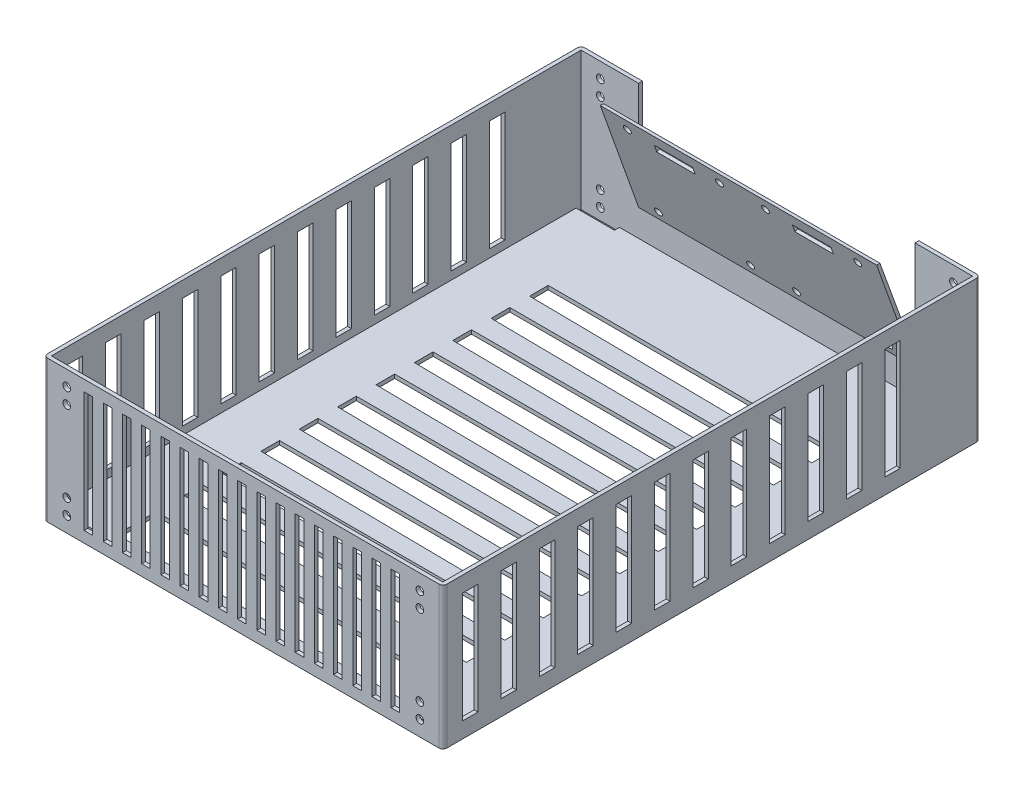
SolidWorks part; units mm, degrees
ref_plane "Front Plane" through (0, 0, 0) normal (0, 0, 1) x (1, 0, 0)
ref_plane "Top Plane" through (0, 0, 0) normal (0, 1, 0) x (1, 0, 0)
ref_plane "Right Plane" through (0, 0, 0) normal (1, 0, 0) x (0, 0, -1)
sketch "Sketch2" plane through (0, 0, 0) normal (0, 1, 0) x (1, 0, 0)
  line L1 (-52, -70) -> (52, -70)
  line L2 (-52, -70) -> (-52, 70)
  line L3 (-52, 70) -> (52, 70)
  line L4 (52, -70) -> (52, 70)
  line L5 (-52, -70) -> (52, 70) construction
  line L6 (-52, 70) -> (52, -70) construction
  point P0 (0, 0)
  dimension "D1" = 104
  dimension "D2" = 140
extrude "Boss-Extrude1" add sketch "Sketch2" along normal blind 1
sketch "Sketch3" plane through (0, 1, 0) normal (0, 1, 0) x (1, 0, 0)
  line L10 (-52, 70) -> (52, 70)
  line L11 (52, 70) -> (52, -70)
  line L12 (52, -70) -> (-52, -70)
  line L13 (-52, -70) -> (-52, 70)
  line L18 (-51, -69) -> (51, -69)
  line L19 (51, -69) -> (51, 69)
  line L20 (51, 69) -> (-51, 69)
  line L21 (-51, 69) -> (-51, -69)
  point P4 (0, -70)
  point P5 (0, -69)
  dimension "D2" = 1
  dimension "D1" = 1
  dimension "D3" = 1
  dimension "D4" = 1
extrude "Boss-Extrude2" add sketch "Sketch3" along normal blind 35 and the other way blind 2
sketch "Sketch4" plane through (0, -1, 0) normal (0, -1, 0) x (1, 0, 0)
  line L18 (-51, 69) -> (51, 69)
  line L19 (-51, 69) -> (51, 69) construction
  line L20 (51, 69) -> (51, -69)
  line L21 (51, -69) -> (-51, -69)
  line L22 (-51.5, 69.5) -> (-51.5, -69.5)
  line L23 (-51.5, -69.5) -> (51.5, -69.5)
  line L24 (51.5, 69.5) -> (-51.5, 69.5)
  line L25 (51.5, -69.5) -> (51.5, 69.5)
  line L26 (-51.5, 69.5) -> (-51.5, -69.5)
  line L27 (-51.5, -69.5) -> (51.5, -69.5)
  line L28 (51.5, 69.5) -> (-51.5, 69.5)
  line L29 (51.5, -69.5) -> (51.5, 69.5)
  line L30 (-51, -69) -> (-51, 69)
  dimension "D1" = 0.5
extrude "Cut-Extrude1" cut sketch "Sketch4" against normal blind 1
fillet "Fillet1" radius 1 4 edges at (-52, 17.5, 70) (-52, 17.5, -70) (52, 17.5, -70) (52, 17.5, 70)
sketch "Sketch5" plane through (0, 0, -70) normal (0, 0, -1) x (-1, 0, 0)
  line L0 (51, -1) -> (51, 10)
  line L1 (51, -1) -> (51, 36) construction
  line L2 (51, 10) -> (41, 10)
  line L3 (41, 10) -> (41, -1)
  line L4 (-51, -1) -> (51, -1) construction
  line L5 (41, -1) -> (51, -1)
  line L6 (46, 10) -> (46, -1) construction
  line L7 (41, 3) -> (51, 3) construction
  line L8 (41, 7) -> (51, 7) construction
  line L9 (0, -1) -> (0, 36) construction
  line L10 (-51, 36) -> (51, 36) construction
  line L11 (51, 17.5) -> (0, 17.5) construction
  line L12 (0, 17.5) -> (-51.1366, 17.5) construction
  circle A0 centre (46, 7) radius 1
  circle A1 centre (46, 3) radius 1
  circle A2 centre (-46, 3) radius 1
  circle A3 centre (-46, 7) radius 1
  circle A4 centre (46, 32) radius 1
  circle A5 centre (46, 28) radius 1
  circle A6 centre (-46, 32) radius 1
  circle A7 centre (-46, 28) radius 1
  point P38 (0, 0)
  point P39 (0, 0)
  point P40 (0, 0)
  point P41 (0, 0)
  dimension "D5" = 2
  dimension "D6" = 2
  dimension "D1" = 10
  dimension "D2" = 11
  dimension "D3" = 3
  dimension "D4" = 4
extrude "Cut-Extrude2" cut sketch "Sketch5" against normal through all contours A2 | A0 | A1 | A4 | A3 | A7 | A6 | A5
sketch "Sketch6" plane through (52, 0, 0) normal (1, 0, 0) x (0, 0, -1)
  line L0 (-64.8795, 31.9235) -> (-64.8795, 3.0765)
  line L5 (-64.8795, 3.0765) -> (-60.8489, 3.0765)
  line L6 (-60.8489, 3.0765) -> (-60.8489, 31.9235)
  line L7 (-60.8489, 31.9235) -> (-64.8795, 31.9235)
  line L8 (-62.8642, 36) -> (-62.8642, 31.9235) construction
  line L9 (-69, 36) -> (69, 36) construction
  line L10 (-62.8642, 3.0765) -> (-62.8642, -1) construction
  line L11 (-69, -1) -> (69, -1) construction
  line L12 (-50.8489, 31.9235) -> (-54.8795, 31.9235)
  line L13 (-54.8795, 31.9235) -> (-54.8795, 3.0765)
  line L14 (-54.8795, 3.0765) -> (-50.8489, 3.0765)
  line L15 (-50.8489, 3.0765) -> (-50.8489, 31.9235)
  line L16 (-40.8489, 31.9235) -> (-44.8795, 31.9235)
  line L17 (-44.8795, 31.9235) -> (-44.8795, 3.0765)
  line L18 (-44.8795, 3.0765) -> (-40.8489, 3.0765)
  line L19 (-40.8489, 3.0765) -> (-40.8489, 31.9235)
  line L20 (-30.8489, 31.9235) -> (-34.8795, 31.9235)
  line L21 (-34.8795, 31.9235) -> (-34.8795, 3.0765)
  line L22 (-34.8795, 3.0765) -> (-30.8489, 3.0765)
  line L23 (-30.8489, 3.0765) -> (-30.8489, 31.9235)
  line L24 (-20.8489, 31.9235) -> (-24.8795, 31.9235)
  line L25 (-24.8795, 31.9235) -> (-24.8795, 3.0765)
  line L26 (-24.8795, 3.0765) -> (-20.8489, 3.0765)
  line L27 (-20.8489, 3.0765) -> (-20.8489, 31.9235)
  line L28 (-10.8489, 31.9235) -> (-14.8795, 31.9235)
  line L29 (-14.8795, 31.9235) -> (-14.8795, 3.0765)
  line L30 (-14.8795, 3.0765) -> (-10.8489, 3.0765)
  line L31 (-10.8489, 3.0765) -> (-10.8489, 31.9235)
  line L32 (-0.8489, 31.9235) -> (-4.8795, 31.9235)
  line L33 (-4.8795, 31.9235) -> (-4.8795, 3.0765)
  line L34 (-4.8795, 3.0765) -> (-0.8489, 3.0765)
  line L35 (-0.8489, 3.0765) -> (-0.8489, 31.9235)
  line L36 (9.1511, 31.9235) -> (5.1205, 31.9235)
  line L37 (5.1205, 31.9235) -> (5.1205, 3.0765)
  line L38 (5.1205, 3.0765) -> (9.1511, 3.0765)
  line L39 (9.1511, 3.0765) -> (9.1511, 31.9235)
  line L40 (19.1511, 31.9235) -> (15.1205, 31.9235)
  line L41 (15.1205, 31.9235) -> (15.1205, 3.0765)
  line L42 (15.1205, 3.0765) -> (19.1511, 3.0765)
  line L43 (19.1511, 3.0765) -> (19.1511, 31.9235)
  line L44 (29.1511, 31.9235) -> (25.1205, 31.9235)
  line L45 (25.1205, 31.9235) -> (25.1205, 3.0765)
  line L46 (25.1205, 3.0765) -> (29.1511, 3.0765)
  line L47 (29.1511, 3.0765) -> (29.1511, 31.9235)
  line L48 (39.1511, 31.9235) -> (35.1205, 31.9235)
  line L49 (35.1205, 31.9235) -> (35.1205, 3.0765)
  line L50 (35.1205, 3.0765) -> (39.1511, 3.0765)
  line L51 (39.1511, 3.0765) -> (39.1511, 31.9235)
  line L52 (49.1511, 31.9235) -> (45.1205, 31.9235)
  line L53 (45.1205, 31.9235) -> (45.1205, 3.0765)
  line L54 (45.1205, 3.0765) -> (49.1511, 3.0765)
  line L55 (49.1511, 3.0765) -> (49.1511, 31.9235)
  line L60 (59.1511, 3.0765) -> (59.1511, 31.9235) [skipped]
  line L61 (55.1205, 31.9235) -> (55.1205, 3.0765) [skipped]
  line L62 (55.1205, 3.0765) -> (59.1511, 3.0765) [skipped]
  line L63 (59.1511, 31.9235) -> (55.1205, 31.9235) [skipped]
  point P0 (-64.8795, 31.9235)
  dimension "D1" = 13
extrude "Cut-Extrude3" cut sketch "Sketch6" against normal through all
sketch "Sketch7" plane through (0, 1, 0) normal (0, 1, 0) x (1, 0, 0)
  line L0 (-51, -69) -> (-41, -69)
  line L1 (51, -69) -> (-51, -69) construction
  line L2 (-41, -69) -> (-41, -67.7)
  line L3 (-41, -67.7) -> (-51, -67.7)
  line L4 (-51, -69) -> (-51, 69) construction
  line L5 (-51, -67.7) -> (-51, -69)
  line L6 (0, -69) -> (0, 69) construction
  line L7 (-51, 69) -> (51, 69) construction
  line L8 (51, -67.7) -> (51, -69)
  line L9 (41, -67.7) -> (51, -67.7)
  line L10 (41, -69) -> (41, -67.7)
  line L11 (51, -69) -> (41, -69)
  line L12 (-51, 0) -> (51, 0) construction
  line L13 (51, 69) -> (51, -69) construction
  line L15 (51, 67.7) -> (51, 69)
  line L16 (41, 69) -> (41, 67.7)
  line L17 (41, 67.7) -> (51, 67.7)
  line L18 (51, 69) -> (41, 69)
  line L19 (-51, 67.7) -> (-51, 69)
  line L20 (-41, 67.7) -> (-51, 67.7)
  line L21 (-41, 69) -> (-41, 67.7)
  line L22 (-51, 69) -> (-41, 69)
  dimension "D1" = 1.3
  dimension "D2" = 10
extrude "Cut-Extrude4" cut sketch "Sketch7" against normal through all
sketch "Sketch8" plane through (0, 1, 0) normal (0, 1, 0) x (1, 0, 0)
  line L0 (37.1917, -65.7816) -> (-37.1917, -65.7816)
  line L1 (-37.1917, -65.7816) -> (-37.1917, -55.4496)
  line L2 (-37.1917, -55.4496) -> (37.1917, -56.5504)
  line L3 (37.1917, -56.5504) -> (37.1917, -65.7816)
  line L4 (37.1917, -61.166) -> (51, -61.166) construction
  line L5 (51, 67.7) -> (51, -67.7) construction
  line L6 (-37.1917, -60.6156) -> (-51, -60.6156) construction
  line L7 (-51, -67.7) -> (-51, 67.7) construction
  line L8 (-37.1917, -33.3793) -> (-37.1917, -38.2246)
  line L9 (-41, 69) -> (41, 69) construction
  line L10 (-37.1917, -48.2246) -> (37.1917, -49.0949)
  line L11 (37.1917, -49.0949) -> (37.1917, -43.3793)
  line L12 (37.1917, -43.3793) -> (-37.1917, -43.3793)
  line L13 (-37.1917, -43.3793) -> (-37.1917, -48.2246)
  line L14 (-37.1917, -38.2246) -> (37.1917, -39.0949)
  line L15 (37.1917, -39.0949) -> (37.1917, -33.3793)
  line L16 (37.1917, -33.3793) -> (-37.1917, -33.3793)
  line L17 (-37.1917, -23.3793) -> (-37.1917, -28.2246)
  line L18 (-37.1917, -28.2246) -> (37.1917, -29.0949)
  line L19 (37.1917, -29.0949) -> (37.1917, -23.3793)
  line L20 (37.1917, -23.3793) -> (-37.1917, -23.3793)
  line L21 (-37.1917, -13.3793) -> (-37.1917, -18.2246)
  line L22 (-37.1917, -18.2246) -> (37.1917, -19.0949)
  line L23 (37.1917, -19.0949) -> (37.1917, -13.3793)
  line L24 (37.1917, -13.3793) -> (-37.1917, -13.3793)
  line L25 (-37.1917, -3.3793) -> (-37.1917, -8.2246)
  line L26 (-37.1917, -8.2246) -> (37.1917, -9.0949)
  line L27 (37.1917, -9.0949) -> (37.1917, -3.3793)
  line L28 (37.1917, -3.3793) -> (-37.1917, -3.3793)
  line L29 (-37.1917, 6.6207) -> (-37.1917, 1.7754)
  line L30 (-37.1917, 1.7754) -> (37.1917, 0.9051)
  line L31 (37.1917, 0.9051) -> (37.1917, 6.6207)
  line L32 (37.1917, 6.6207) -> (-37.1917, 6.6207)
  line L33 (-37.1917, 16.6207) -> (-37.1917, 11.7754)
  line L34 (-37.1917, 11.7754) -> (37.1917, 10.9051)
  line L35 (37.1917, 10.9051) -> (37.1917, 16.6207)
  line L36 (37.1917, 16.6207) -> (-37.1917, 16.6207)
  line L37 (-37.1917, 26.6207) -> (-37.1917, 21.7754)
  line L38 (-37.1917, 21.7754) -> (37.1917, 20.9051)
  line L39 (37.1917, 20.9051) -> (37.1917, 26.6207)
  line L40 (37.1917, 26.6207) -> (-37.1917, 26.6207)
  line L41 (-37.1917, 36.6207) -> (-37.1917, 31.7754)
  line L42 (-37.1917, 31.7754) -> (37.1917, 30.9051)
  line L43 (37.1917, 30.9051) -> (37.1917, 36.6207)
  line L44 (37.1917, 36.6207) -> (-37.1917, 36.6207)
  line L45 (-37.1917, 46.6207) -> (-37.1917, 41.7754)
  line L46 (-37.1917, 41.7754) -> (37.1917, 40.9051)
  line L47 (37.1917, 40.9051) -> (37.1917, 46.6207)
  line L48 (37.1917, 46.6207) -> (-37.1917, 46.6207)
  point P12 (0, -56)
  dimension "D1" = 125
  dimension "D2" = 10
extrude "Cut-Extrude5" cut sketch "Sketch8" against normal blind 10
sketch "Sketch9" plane through (0, 0, -70) normal (0, 0, -1) x (-1, 0, 0)
  line L0 (0, 36) -> (36, 36)
  line L1 (-51, 36) -> (51, 36) construction
  line L2 (36, 36) -> (36, 8)
  line L3 (36, 8) -> (-36, 8)
  line L4 (-36, 8) -> (-36, 36)
  line L5 (-36, 36) -> (0, 36)
  dimension "D1" = 36
  dimension "D2" = 36
  dimension "D3" = 28
extrude "Cut-Extrude9" cut sketch "Sketch9" against normal blind 72
sketch "Sketch11" plane through (-36, 0, 0) normal (1, 0, 0) x (0, 0, -1)
  line L1 (59.8427, 36) -> (59, 36)
  line L2 (59, 36) -> (69, 8)
  line L5 (69, 8) -> (70, 8)
  line L6 (60.1966, 35.0243) -> (70, 8)
  line L7 (60.1966, 35.0243) -> (59.8427, 36)
  point P1 (0, 0)
  dimension "D1" = 10
extrude "Boss-Extrude3" add sketch "Sketch11" along normal blind 72
sketch "Sketch12" plane through (0, 23.3706, -64.4241) normal (0, 0.341, -0.9401) x (-1, 0, 0)
  line L0 (0, 13.4347) -> (0, -16.3507) construction
  line L1 (-36, 13.4347) -> (36, 13.4347) construction
  line L2 (-36, -16.3507) -> (36, -16.3507) construction
  line L3 (0, -1.458) -> (36, -1.458) construction
  line L6 (36, -13.4183) -> (36, 13.4347) construction
  line L7 (36, -1.458) -> (-36, -1.458) construction
  line L8 (-36, -13.4183) -> (-36, 13.4347) construction
  line L9 (6, 5.5502) -> (0, 5.5502) construction
  line L10 (6, -13.458) -> (30, -13.458) construction
  line L11 (6, -13.458) -> (6, 10.542) construction
  line L12 (6, 10.542) -> (30, 10.542) construction
  line L13 (30, -13.458) -> (30, 10.542) construction
  line L14 (6, -13.458) -> (30, 10.542) construction
  line L15 (6, 10.542) -> (30, -13.458) construction
  line L16 (30, 5.5502) -> (36, 5.5502) construction
  line L17 (18, 10.542) -> (23, 10.542)
  line L18 (23, 10.542) -> (23, 8.542)
  line L19 (23, 8.542) -> (13, 8.542)
  line L20 (13, 8.542) -> (13, 10.542)
  line L21 (13, 10.542) -> (18, 10.542)
  line L22 (-13, 8.542) -> (-13, 10.542)
  line L23 (-23, 8.542) -> (-13, 8.542)
  line L24 (-23, 10.542) -> (-23, 8.542)
  line L25 (-18, 10.542) -> (-23, 10.542)
  line L26 (-13, 10.542) -> (-18, 10.542)
  circle A0 centre (30, 10.542) radius 1
  circle A1 centre (30, -13.458) radius 1
  circle A2 centre (6, -13.458) radius 1
  circle A3 centre (6, 10.542) radius 1
  circle A4 centre (-30, 10.542) radius 1
  circle A5 centre (-30, -13.458) radius 1
  circle A6 centre (-6, -13.458) radius 1
  circle A7 centre (-6, 10.542) radius 1
  point P10 (18, -1.458)
  dimension "D3" = 2
  dimension "D1" = 24
  dimension "D2" = 24
  dimension "D4" = 5
  dimension "D5" = 5
  dimension "D6" = 2
extrude "Cut-Extrude10" cut sketch "Sketch12" against normal blind 12
sketch "Sketch13" plane through (0, 0, 70) normal (0, 0, 1) x (1, 0, 0)
  line L0 (-40.3725, 33.1402) -> (-40.3725, 36) construction
  line L1 (-39.2556, 1.8598) -> (-41.4894, 1.8598)
  line L2 (-39.2556, 1.8598) -> (-39.2556, 33.1402)
  line L3 (-39.2556, 33.1402) -> (-41.4894, 33.1402)
  line L4 (-41.4894, 1.8598) -> (-41.4894, 33.1402)
  line L5 (-39.2556, 1.8598) -> (-41.4894, 33.1402) construction
  line L6 (-39.2556, 33.1402) -> (-41.4894, 1.8598) construction
  line L7 (-51, 36) -> (51, 36) construction
  line L8 (-40.3725, 1.8598) -> (-40.3725, -1) construction
  line L9 (-51, -1) -> (51, -1) construction
  line L10 (-34.2556, 1.8598) -> (-34.2556, 33.1402)
  line L11 (-36.4894, 1.8598) -> (-36.4894, 33.1402)
  line L12 (-34.2556, 33.1402) -> (-36.4894, 33.1402)
  line L13 (-34.2556, 1.8598) -> (-36.4894, 1.8598)
  line L14 (-29.2556, 1.8598) -> (-29.2556, 33.1402)
  line L15 (-31.4894, 1.8598) -> (-31.4894, 33.1402)
  line L16 (-29.2556, 33.1402) -> (-31.4894, 33.1402)
  line L17 (-29.2556, 1.8598) -> (-31.4894, 1.8598)
  line L18 (-24.2556, 1.8598) -> (-24.2556, 33.1402)
  line L19 (-26.4894, 1.8598) -> (-26.4894, 33.1402)
  line L20 (-24.2556, 33.1402) -> (-26.4894, 33.1402)
  line L21 (-24.2556, 1.8598) -> (-26.4894, 1.8598)
  line L22 (-19.2556, 1.8598) -> (-19.2556, 33.1402)
  line L23 (-21.4894, 1.8598) -> (-21.4894, 33.1402)
  line L24 (-19.2556, 33.1402) -> (-21.4894, 33.1402)
  line L25 (-19.2556, 1.8598) -> (-21.4894, 1.8598)
  line L26 (-14.2556, 1.8598) -> (-14.2556, 33.1402)
  line L27 (-16.4894, 1.8598) -> (-16.4894, 33.1402)
  line L28 (-14.2556, 33.1402) -> (-16.4894, 33.1402)
  line L29 (-14.2556, 1.8598) -> (-16.4894, 1.8598)
  line L30 (-9.2556, 1.8598) -> (-9.2556, 33.1402)
  line L31 (-11.4894, 1.8598) -> (-11.4894, 33.1402)
  line L32 (-9.2556, 33.1402) -> (-11.4894, 33.1402)
  line L33 (-9.2556, 1.8598) -> (-11.4894, 1.8598)
  line L34 (-4.2556, 1.8598) -> (-4.2556, 33.1402)
  line L35 (-6.4894, 1.8598) -> (-6.4894, 33.1402)
  line L36 (-4.2556, 33.1402) -> (-6.4894, 33.1402)
  line L37 (-4.2556, 1.8598) -> (-6.4894, 1.8598)
  line L38 (0.7444, 1.8598) -> (0.7444, 33.1402)
  line L39 (-1.4894, 1.8598) -> (-1.4894, 33.1402)
  line L40 (0.7444, 33.1402) -> (-1.4894, 33.1402)
  line L41 (0.7444, 1.8598) -> (-1.4894, 1.8598)
  line L42 (5.7444, 1.8598) -> (5.7444, 33.1402)
  line L43 (3.5106, 1.8598) -> (3.5106, 33.1402)
  line L44 (5.7444, 33.1402) -> (3.5106, 33.1402)
  line L45 (5.7444, 1.8598) -> (3.5106, 1.8598)
  line L46 (10.7444, 1.8598) -> (10.7444, 33.1402)
  line L47 (8.5106, 1.8598) -> (8.5106, 33.1402)
  line L48 (10.7444, 33.1402) -> (8.5106, 33.1402)
  line L49 (10.7444, 1.8598) -> (8.5106, 1.8598)
  line L50 (15.7444, 1.8598) -> (15.7444, 33.1402)
  line L51 (13.5106, 1.8598) -> (13.5106, 33.1402)
  line L52 (15.7444, 33.1402) -> (13.5106, 33.1402)
  line L53 (15.7444, 1.8598) -> (13.5106, 1.8598)
  line L54 (20.7444, 1.8598) -> (20.7444, 33.1402)
  line L55 (18.5106, 1.8598) -> (18.5106, 33.1402)
  line L56 (20.7444, 33.1402) -> (18.5106, 33.1402)
  line L57 (20.7444, 1.8598) -> (18.5106, 1.8598)
  line L58 (25.7444, 1.8598) -> (25.7444, 33.1402)
  line L59 (23.5106, 1.8598) -> (23.5106, 33.1402)
  line L60 (25.7444, 33.1402) -> (23.5106, 33.1402)
  line L61 (25.7444, 1.8598) -> (23.5106, 1.8598)
  line L62 (30.7444, 1.8598) -> (30.7444, 33.1402)
  line L63 (28.5106, 1.8598) -> (28.5106, 33.1402)
  line L64 (30.7444, 33.1402) -> (28.5106, 33.1402)
  line L65 (30.7444, 1.8598) -> (28.5106, 1.8598)
  line L66 (35.7444, 1.8598) -> (35.7444, 33.1402)
  line L67 (33.5106, 1.8598) -> (33.5106, 33.1402)
  line L68 (35.7444, 33.1402) -> (33.5106, 33.1402)
  line L69 (35.7444, 1.8598) -> (33.5106, 1.8598)
  line L70 (40.7444, 1.8598) -> (40.7444, 33.1402)
  line L71 (38.5106, 1.8598) -> (38.5106, 33.1402)
  line L72 (40.7444, 33.1402) -> (38.5106, 33.1402)
  line L73 (40.7444, 1.8598) -> (38.5106, 1.8598)
  point P0 (-40.3725, 17.5)
  dimension "D1" = 17
extrude "Cut-Extrude11" cut sketch "Sketch13" against normal blind 12
